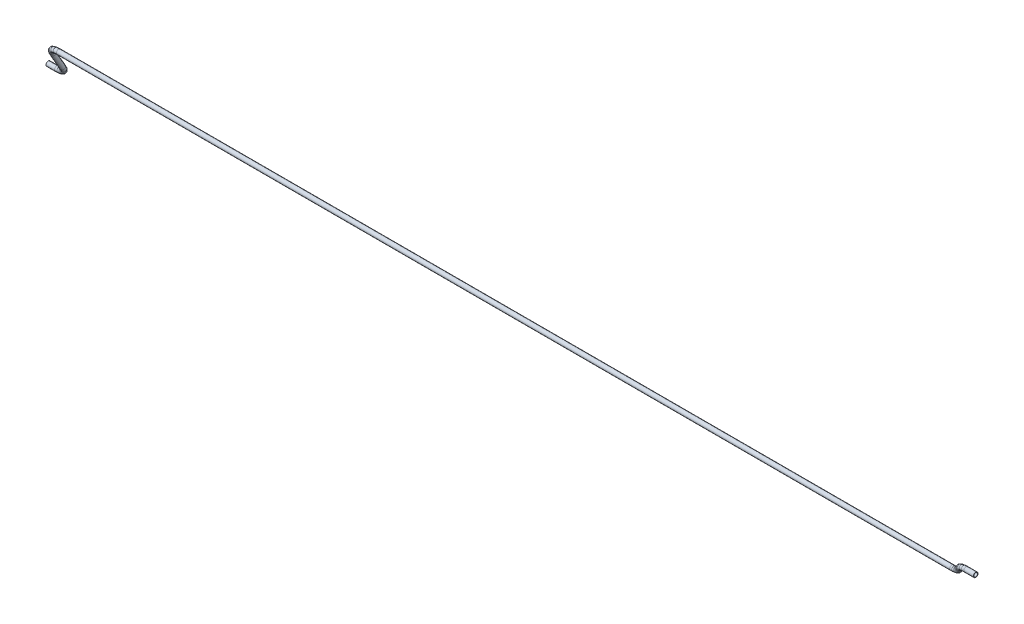
SolidWorks part; units mm, degrees
ref_plane "Front Plane" through (0, 0, 0) normal (0, 0, 1) x (1, 0, 0)
ref_plane "Top Plane" through (0, 0, 0) normal (0, 1, 0) x (1, 0, 0)
ref_plane "Right Plane" through (0, 0, 0) normal (1, 0, 0) x (0, 0, -1)
sketch3d "Path"
  line L0 (-2155.188, 0, 0) -> (-2137.388, 0, 0)
  line L1 (-2137.388, 0, 0) -> (-2131.1763, 0.7082, 0.4089)
  line L2 (-2131.1763, 0.7082, 0.4089) -> (-2125.388, 2.7846, 1.6077)
  line L3 (-2125.388, 2.7846, 1.6077) -> (-2120.4174, 6.0877, 3.5147)
  line L4 (-2120.4174, 6.0877, 3.5147) -> (-2116.6034, 10.3923, 6)
  line L5 (-2116.6034, 10.3923, 6) -> (-2114.2057, 15.4052, 8.8942)
  line L6 (-2114.2057, 15.4052, 8.8942) -> (-2113.388, 20.7846, 12)
  line L7 (-2113.388, 20.7846, 12) -> (-2113.388, 55.4256, 32)
  line L8 (-2113.388, 55.4256, 32) -> (-2112.5702, 60.8051, 35.1058)
  line L9 (-2112.5702, 60.8051, 35.1058) -> (-2110.1726, 65.8179, 38)
  line L10 (-2110.1726, 65.8179, 38) -> (-2106.3585, 70.1226, 40.4853)
  line L11 (-2106.3585, 70.1226, 40.4853) -> (-2101.388, 73.4256, 42.3923)
  line L12 (-2101.388, 73.4256, 42.3923) -> (-2095.5996, 75.502, 43.5911)
  line L13 (-2095.5996, 75.502, 43.5911) -> (-2089.388, 76.2102, 44)
  line L14 (-2089.388, 76.2102, 44) -> (-232.8999, 76.2102, 44)
  line L15 (-232.8999, 76.2102, 44) -> (-228.1788, 76.6163, 44.2345)
  line L16 (-228.1788, 76.6163, 44.2345) -> (-223.6422, 77.8188, 44.9287)
  line L17 (-223.6422, 77.8188, 44.9287) -> (-219.4673, 79.7706, 46.0556)
  line L18 (-219.4673, 79.7706, 46.0556) -> (-215.8174, 82.3955, 47.5711)
  line L19 (-215.8174, 82.3955, 47.5711) -> (-212.835, 85.5909, 49.4159)
  line L20 (-212.835, 85.5909, 49.4159) -> (-210.6367, 89.232, 51.5181)
  line L21 (-210.6367, 89.232, 51.5181) -> (-210.2632, 90.0353, 51.9819)
  line L22 (-210.2632, 90.0353, 51.9819) -> (-208.0649, 93.6764, 54.0841)
  line L23 (-208.0649, 93.6764, 54.0841) -> (-205.0825, 96.8718, 55.9289)
  line L24 (-205.0825, 96.8718, 55.9289) -> (-201.4326, 99.4967, 57.4444)
  line L25 (-201.4326, 99.4967, 57.4444) -> (-197.2577, 101.4485, 58.5713)
  line L26 (-197.2577, 101.4485, 58.5713) -> (-192.7211, 102.6509, 59.2655)
  line L27 (-192.7211, 102.6509, 59.2655) -> (-188, 103.057, 59.5)
  line L28 (-188, 103.057, 59.5) -> (-168.2, 103.057, 59.5)
ref_plane "Start Plane" through (-2155.188, 0, 0) normal (1, 0, 0) x (0, 0, -1)
sketch "Profile" plane through (-2155.188, 0, 0) normal (1, 0, 0) x (0, 0, -1)
  circle A0 centre (0, 0) radius 4.7625
  circle A1 centre (0, 0) radius 3.8735
sweep "Tube" add profiles "Profile" path "Path"
